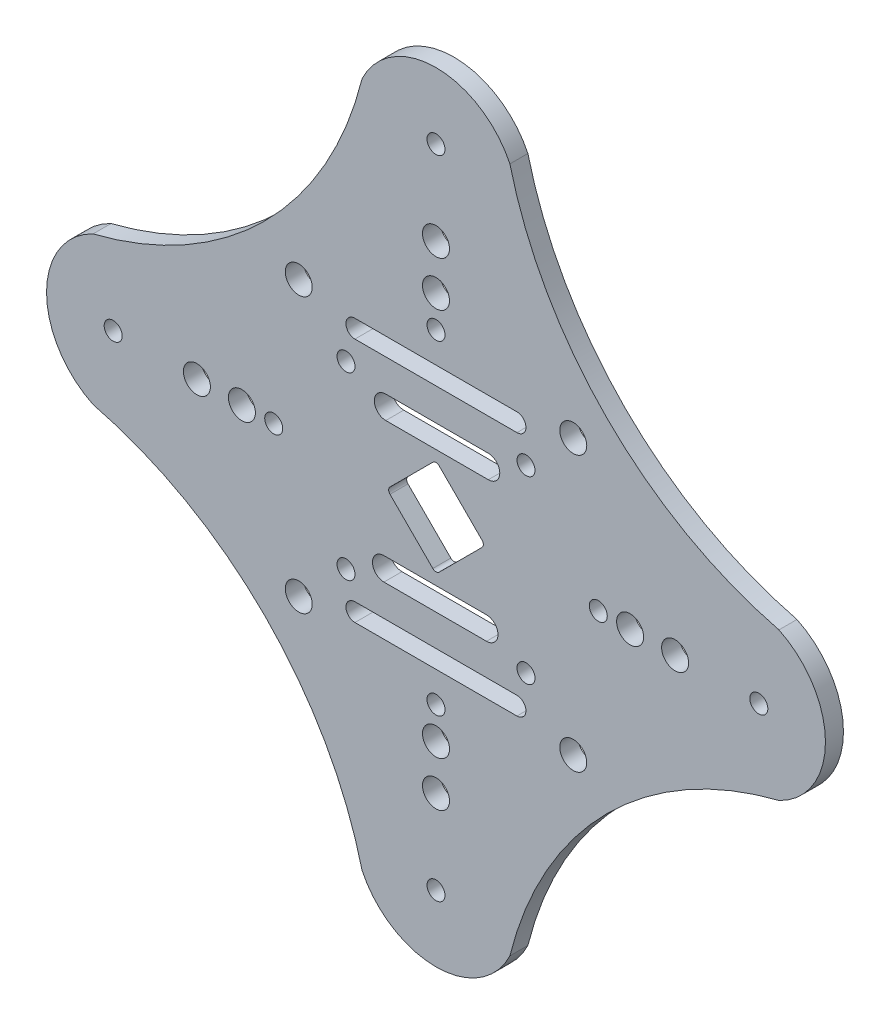
SolidWorks part; units mm, degrees
ref_plane "前视基准面" through (0, 0, 0) normal (0, 0, 1) x (1, 0, 0)
ref_plane "上视基准面" through (0, 0, 0) normal (0, 1, 0) x (1, 0, 0)
ref_plane "右视基准面" through (0, 0, 0) normal (1, 0, 0) x (0, 0, -1)
sketch "Model" plane through (0, 0, 0) normal (0, 0, 1) x (1, 0, 0)
  line L0 (152.3985, 91.0069) -> (141.0047, 91.0069)
  line L1 (141.0047, 93.554) -> (152.3985, 93.554)
  line L2 (152.5997, 109.1993) -> (141.2059, 109.1993)
  line L3 (141.2059, 106.6522) -> (152.5997, 106.6522)
  line L4 (151.8986, 100.4934) -> (147.1408, 105.2512)
  line L5 (146.4337, 105.2512) -> (141.6759, 100.4934)
  line L6 (141.6759, 99.7863) -> (146.4337, 95.0285)
  line L7 (147.1408, 95.0285) -> (151.8986, 99.7863)
  line L8 (137.7799, 87.5035) -> (155.7799, 87.5035)
  line L9 (155.7799, 85.5035) -> (137.7799, 85.5035)
  line L10 (137.7799, 112.7762) -> (155.7799, 112.7762)
  line L11 (155.7799, 114.7762) -> (137.7799, 114.7762)
  circle A0 centre (156.7872, 110.1398) radius 1
  circle A1 centre (136.7872, 110.1398) radius 1
  circle A2 centre (136.7872, 90.1398) radius 1
  circle A3 centre (156.7872, 90.1398) radius 1
  circle A4 centre (168.354, 100.1398) radius 1.5
  circle A5 centre (146.7872, 121.7066) radius 1.5
  circle A6 centre (125.2205, 100.1398) radius 1.5
  circle A7 centre (146.7872, 78.5731) radius 1.5
  circle A8 centre (146.7872, 126.7066) radius 1.5
  circle A9 centre (120.2205, 100.1398) radius 1.5
  circle A10 centre (146.7872, 73.5731) radius 1.5
  circle A11 centre (173.354, 100.1398) radius 1.5
  circle A12 centre (146.7872, 118.171) radius 1
  circle A13 centre (128.756, 100.1398) radius 1
  circle A14 centre (146.7872, 82.1086) radius 1
  circle A15 centre (164.8184, 100.1398) radius 1
  circle A16 centre (162.0372, 115.3898) radius 1.5
  circle A17 centre (131.5372, 115.3898) radius 1.5
  circle A18 centre (131.5372, 84.8898) radius 1.5
  circle A19 centre (162.0372, 84.8898) radius 1.5
  arc A20 (165.7942, 119.1469) -> (184.891, 108.3501) centre (194.7856, 148.1382) ccw
  arc A21 (154.9975, 138.2436) -> (165.7942, 119.1469) centre (194.7856, 148.1382) ccw
  arc A22 (127.7802, 119.1469) -> (138.577, 138.2436) centre (98.7888, 148.1382) ccw
  arc A23 (108.6834, 108.3501) -> (127.7802, 119.1469) centre (98.7888, 148.1382) ccw
  arc A24 (127.7802, 81.1328) -> (108.6834, 91.9296) centre (98.7888, 52.1414) ccw
  arc A25 (138.577, 62.036) -> (127.7802, 81.1328) centre (98.7888, 52.1414) ccw
  arc A26 (165.7942, 81.1328) -> (154.9975, 62.036) centre (194.7856, 52.1414) ccw
  arc A27 (184.891, 91.9296) -> (165.7942, 81.1328) centre (194.7856, 52.1414) ccw
  arc A28 (184.891, 91.9296) -> (184.891, 108.3501) centre (180.9546, 100.1398) ccw
  arc A29 (154.9975, 138.2436) -> (138.577, 138.2436) centre (146.7872, 134.3072) ccw
  arc A30 (108.6834, 108.3501) -> (108.6834, 91.9296) centre (112.6199, 100.1398) ccw
  arc A31 (138.577, 62.036) -> (154.9975, 62.036) centre (146.7872, 65.9725) ccw
  arc A32 (139.7312, 92.2804) -> (141.0047, 91.0069) centre (141.0047, 92.2804) ccw
  arc A33 (152.3985, 91.0069) -> (152.3985, 93.554) centre (152.3985, 92.2804) ccw
  arc A34 (141.0047, 93.554) -> (139.7312, 92.2804) centre (141.0047, 92.2804) ccw
  arc A35 (141.2059, 109.1993) -> (139.9324, 107.9258) centre (141.2059, 107.9258) ccw
  arc A36 (152.5997, 106.6522) -> (152.5997, 109.1993) centre (152.5997, 107.9258) ccw
  arc A37 (139.9324, 107.9258) -> (141.2059, 106.6522) centre (141.2059, 107.9258) ccw
  arc A38 (151.8986, 99.7863) -> (151.8986, 100.4934) centre (151.545, 100.1398) ccw
  arc A39 (147.1408, 105.2512) -> (146.4337, 105.2512) centre (146.7872, 104.8976) ccw
  arc A40 (141.6759, 100.4934) -> (141.6759, 99.7863) centre (142.0294, 100.1398) ccw
  arc A41 (146.4337, 95.0285) -> (147.1408, 95.0285) centre (146.7872, 95.382) ccw
  circle A42 centre (182.6572, 100.1398) radius 1
  circle A43 centre (146.7872, 136.0369) radius 1
  circle A44 centre (110.9172, 100.1398) radius 1
  circle A45 centre (146.7872, 64.2428) radius 1
  arc A46 (137.7799, 87.5035) -> (136.7799, 86.5035) centre (137.7799, 86.5035) ccw
  arc A47 (155.7799, 85.5035) -> (155.7799, 87.5035) centre (155.7799, 86.5035) ccw
  arc A48 (136.7799, 86.5035) -> (137.7799, 85.5035) centre (137.7799, 86.5035) ccw
  arc A49 (136.7799, 113.7762) -> (137.7799, 112.7762) centre (137.7799, 113.7762) ccw
  arc A50 (155.7799, 112.7762) -> (155.7799, 114.7762) centre (155.7799, 113.7762) ccw
  arc A51 (137.7799, 114.7762) -> (136.7799, 113.7762) centre (137.7799, 113.7762) ccw
  spline S0 degree 3 poles (0, 0) (0.3333, 0) (0.6667, 0) (1, 0) knots 0 0 0 0 1 1 1 1
  spline S1 degree 3 poles (0, 0) (0.3333, 0) (0.6667, 0) (1, 0) knots 0 0 0 0 1 1 1 1
extrude "凸台-拉伸1" add sketch "Model" along normal blind 2 contours S0 S1 | A6 | A5 | A4 | A3 | A2 | A1 | A0 | A14 | A13 | A12 | A11 | A10 | A9 | A8 | A7 | A20 A28 A27 A26 A31 A25 A24 A30 A23 A22 A29 A21 | A19 | A18 | A17 | A16 | A15 | L4 A39 L5 A40 L6 A41 L7 A38 | L2 A35 A37 L3 A36 | L0 A32 A34 L1 A33 | A45 | A44 | A43 | A42 | L10 A50 L11 A51 A49 | L8 A47 L9 A48 A46
